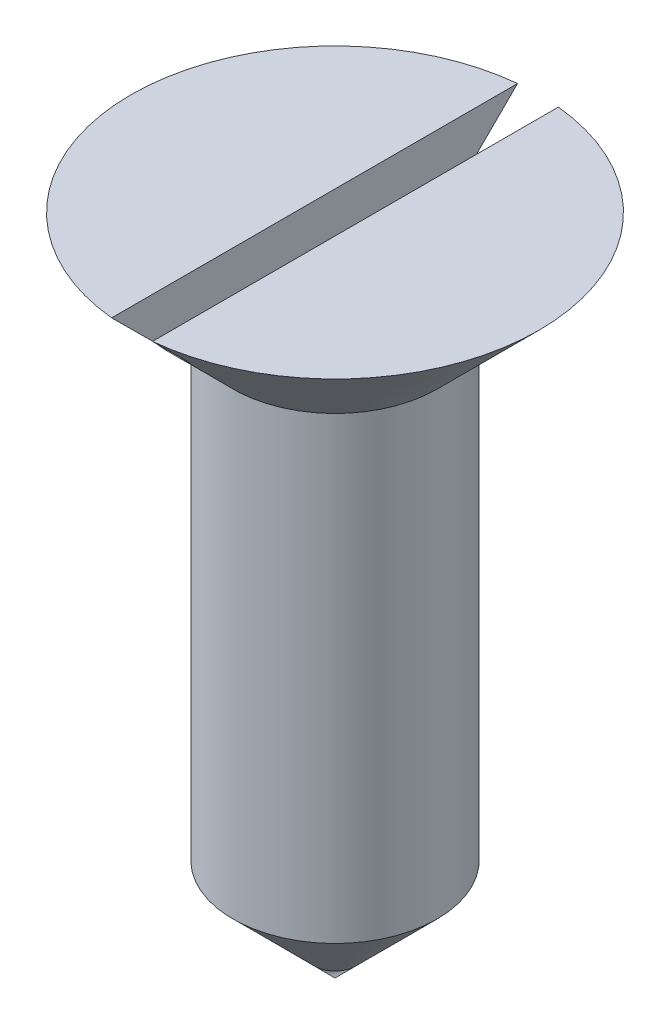
SolidWorks part; units mm, degrees
ref_plane "Front Plane" through (0, 0, 0) normal (0, 0, 1) x (1, 0, 0)
ref_plane "Top Plane" through (0, 0, 0) normal (0, 1, 0) x (1, 0, 0)
ref_plane "Right Plane" through (0, 0, 0) normal (1, 0, 0) x (0, 0, -1)
sketch "Sketch1" plane through (0, 0, 0) normal (0, 0, 1) x (1, 0, 0)
  line L0 (0, 0) -> (6, 6)
  line L1 (6, 6) -> (6, 33)
  line L2 (6, 33) -> (12, 39)
  line L3 (12, 39) -> (0, 39)
  line L4 (0, 39) -> (0, 0)
  line L5 (6, 33) -> (0, 33) construction
  dimension "D1" = 6
  dimension "D2" = 27
  dimension "D3" = 135
  dimension "D4" = 6
revolve "Revolve1" add sketch "Sketch1" angle 360 about L4
sketch "Sketch2" plane through (0, 0, 0) normal (0, 0, 1) x (1, 0, 0)
  line L0 (0, 0) -> (0, 49.2494) construction
  line L1 (12, 39) -> (-12, 39) construction
  line L2 (-1.2, 39) -> (1.2, 39)
  line L3 (-1.2, 39) -> (-1.2, 36.6)
  line L4 (-1.2, 36.6) -> (1.2, 36.6)
  line L5 (1.2, 39) -> (1.2, 36.6)
  dimension "D1" = 2.4
  dimension "D2" = 2.4
extrude "Cut-Extrude1" cut sketch "Sketch2" against normal through all both and the other way through all
